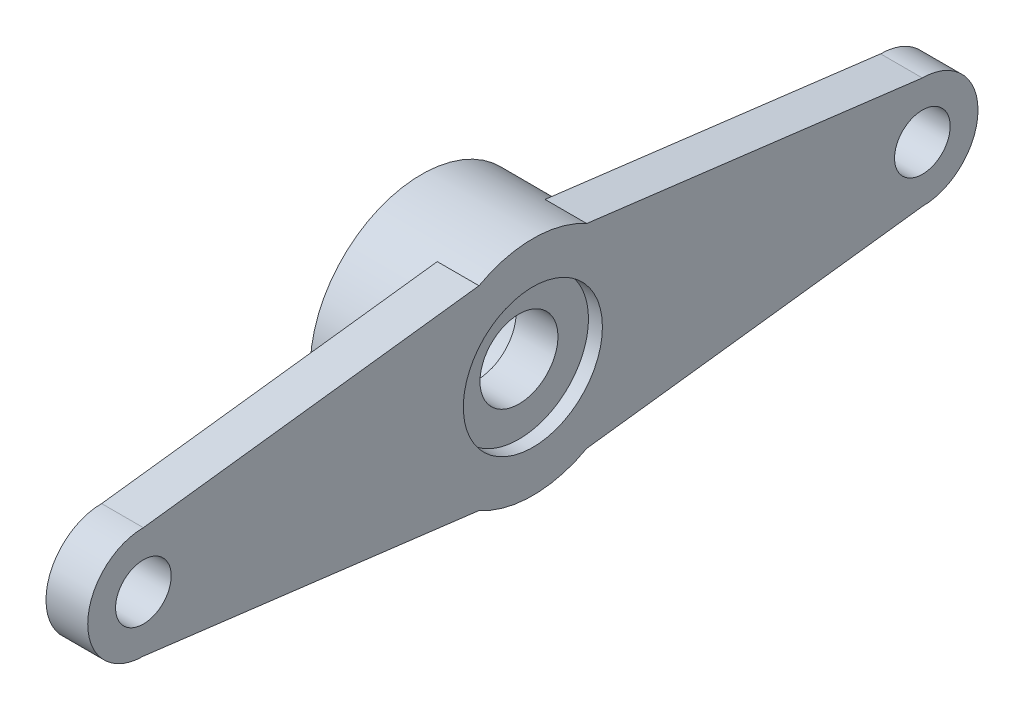
SolidWorks part; units mm, degrees
ref_plane "Front Plane" through (0, 0, 0) normal (0, 0, 1) x (1, 0, 0)
ref_plane "Top Plane" through (0, 0, 0) normal (0, 1, 0) x (1, 0, 0)
ref_plane "Right Plane" through (0, 0, 0) normal (1, 0, 0) x (0, 0, -1)
sketch "Sketch2" plane through (0, 0, 0) normal (1, 0, 0) x (0, 0, -1)
  circle A0 centre (0, 0) radius 4
  circle A1 centre (0, 0) radius 2.5
  dimension "D1" = 5
  dimension "D2" = 8
extrude "Boss-Extrude1" add sketch "Sketch2" along normal blind 2.5
sketch "Sketch3" plane through (2.5, 0, 0) normal (1, 0, 0) x (0, 0, -1)
  line L0 (-7.7364, 3.5) -> (9.9284, 3.5) construction
  line L1 (18.18, 0) -> (-2.5, 0) construction
  line L2 (-7.7364, -3.5) -> (9.9284, -3.5) construction
  line L3 (-1.9365, -3.5) -> (-14, -2)
  line L4 (-14, 2) -> (-1.9365, 3.5)
  line L5 (14, 2) -> (1.9365, 3.5)
  line L6 (14, -2) -> (1.9365, -3.5)
  line L7 (-4, 0) -> (-22.5058, 0) construction
  arc A0 (-14, 2) -> (-14, -2) centre (-14, 0) ccw
  arc A1 (14, -2) -> (14, 2) centre (14, 0) ccw
  circle A2 centre (0, 0) radius 2.5
  arc A3 (1.9365, 3.5) -> (-1.9365, 3.5) centre (0, 0) ccw
  arc A4 (-1.9365, -3.5) -> (1.9365, -3.5) centre (0, 0) ccw
  circle A5 centre (-14, 0) radius 1
  circle A6 centre (14, 0) radius 1
  dimension "D1" = 4
  dimension "D6" = 2
  dimension "D2" = 3.5
  dimension "D3" = 7
  dimension "D4" = 14
  dimension "D5" = 14
extrude "Boss-Extrude2" add sketch "Sketch3" along normal blind 1.5
sketch "Sketch4" plane through (0, 0, 0) normal (-1, 0, 0) x (0, 0, 1)
  circle A0 centre (0, 0) radius 2.5
  circle A1 centre (0, 0) radius 1.4009
extrude "Boss-Extrude3" add sketch "Sketch4" against normal blind 3.5 separate body
sketch "Sketch5" plane through (0, 0, 0) normal (1, 0, 0) x (0, 0, -1)
  circle A0 centre (0, 0) radius 2.5
sketch "Sketch6" plane through (0, 0, 0) normal (-1, 0, 0) x (0, 0, 1)
  circle A0 centre (0, 0) radius 2.5
extrude "Cut-Extrude2" cut sketch "Sketch6" against normal blind 2
